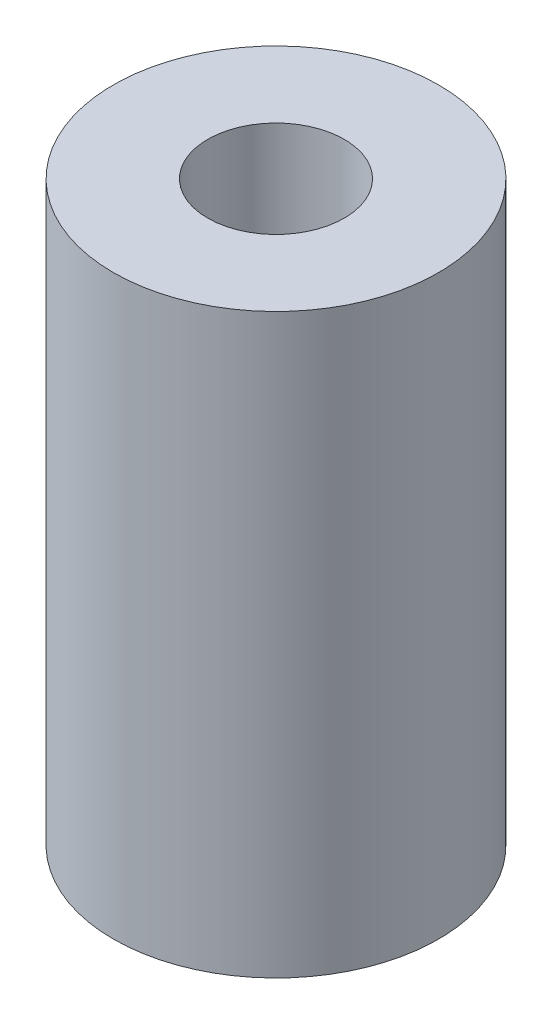
SolidWorks part; units mm, degrees
ref_plane "Front Plane" through (0, 0, 0) normal (0, 0, 1) x (1, 0, 0)
ref_plane "Top Plane" through (0, 0, 0) normal (0, 1, 0) x (1, 0, 0)
ref_plane "Right Plane" through (0, 0, 0) normal (1, 0, 0) x (0, 0, -1)
sketch "Sketch2" plane through (0, 0, 0) normal (0, 1, 0) x (1, 0, 0)
  circle A0 centre (0, 0) radius 5
  circle A1 centre (0, 0) radius 2.1
  dimension "D1" = 4.2
  dimension "D2" = 10
extrude "Boss-Extrude1" add sketch "Sketch2" along normal blind 17.75
